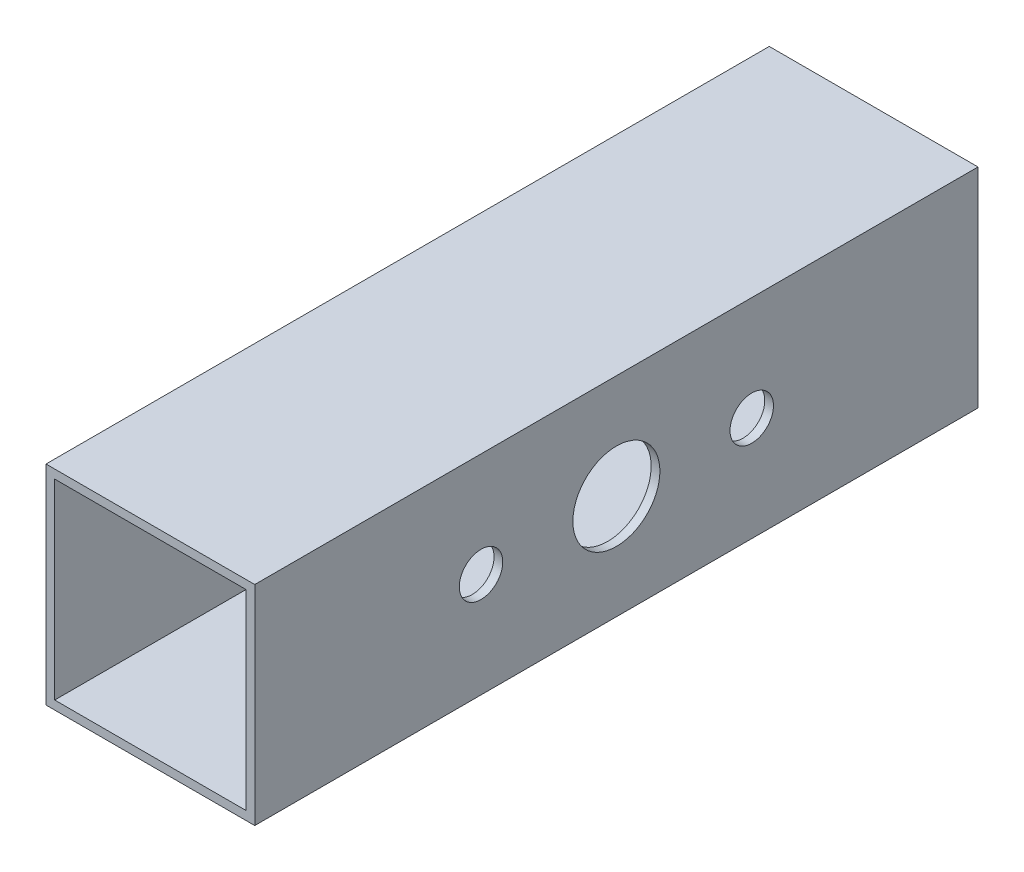
SolidWorks part; units mm, degrees
ref_plane "Front Plane" through (0, 0, 0) normal (0, 0, 1) x (1, 0, 0)
ref_plane "Top Plane" through (0, 0, 0) normal (0, 1, 0) x (1, 0, 0)
ref_plane "Right Plane" through (0, 0, 0) normal (1, 0, 0) x (0, 0, -1)
sketch "Sketch1" plane through (0, 0, 0) normal (0, 0, 1) x (1, 0, 0)
  line L0 (-38.1, -38.1) -> (-38.1, 38.1)
  line L1 (-34.925, -34.925) -> (34.925, -34.925)
  line L2 (-34.925, -34.925) -> (-34.925, 34.925)
  line L3 (-34.925, 34.925) -> (34.925, 34.925)
  line L4 (34.925, -34.925) -> (34.925, 34.925)
  line L5 (-34.925, -34.925) -> (34.925, 34.925) construction
  line L6 (-34.925, 34.925) -> (34.925, -34.925) construction
  line L7 (-38.1, 38.1) -> (38.1, 38.1)
  line L8 (38.1, -38.1) -> (38.1, 38.1)
  line L9 (-38.1, -38.1) -> (38.1, -38.1)
  point P0 (0, 0)
  dimension "D1" = 76.2
  dimension "D2" = 3.175
extrude "Boss-Extrude1" add sketch "Sketch1" along normal mid plane 264 contours L1 L4 L3 L2 | L7 L8 L9 L0
sketch "Sketch2" plane through (-38.1, 0, 0) normal (-1, 0, 0) x (0, 0, 1)
  line L0 (-49.4109, 0) -> (49.4109, 0) construction
  circle A0 centre (0, 0) radius 15.875
  circle A1 centre (-49.4109, 0) radius 7.9375
  circle A2 centre (49.4109, 0) radius 7.9375
  point P6 (0, 0)
  point P8 (0, 0)
  dimension "D1" = 31.75
  dimension "D2" = 98.8219
  dimension "D3" = 15.875
  dimension "D4" = 15.875
extrude "Cut-Extrude1" cut sketch "Sketch2" against normal through all contours A0 | A2 | A1
